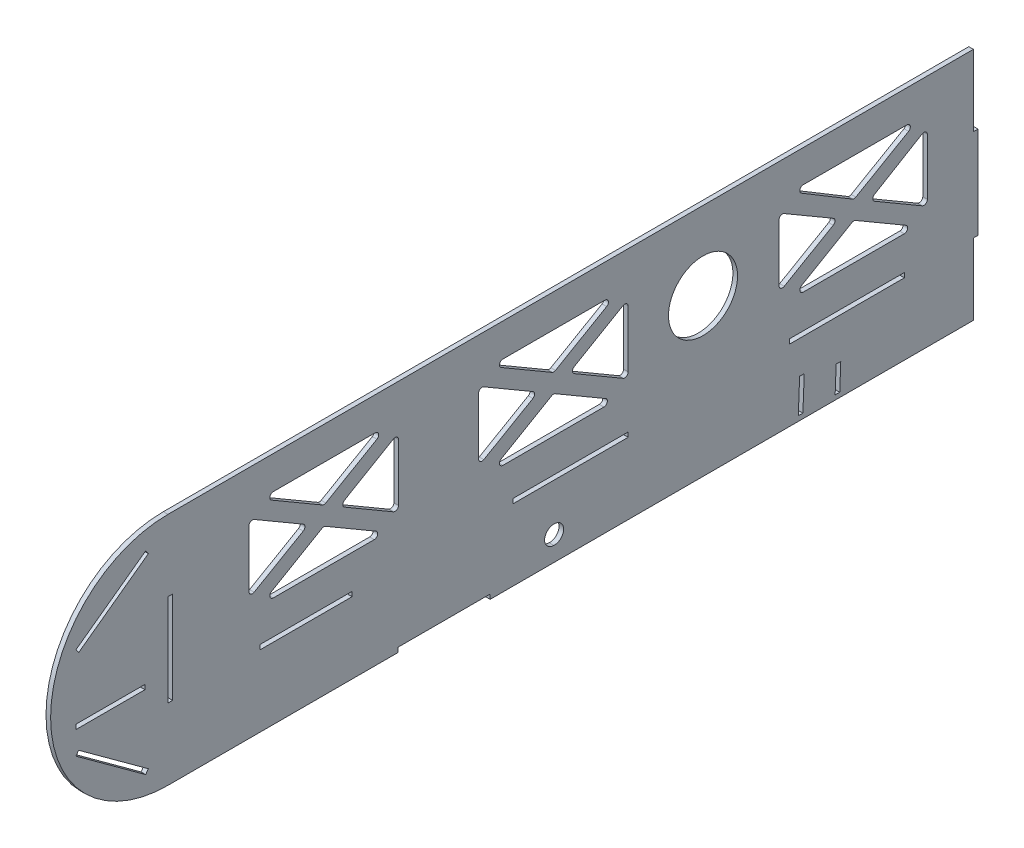
SolidWorks part; units mm, degrees
material "轻木"
ref_plane "前视基准面" through (0, 0, 0) normal (0, 0, 1) x (1, 0, 0)
ref_plane "上视基准面" through (0, 0, 0) normal (0, 1, 0) x (1, 0, 0)
ref_plane "右视基准面" through (0, 0, 0) normal (1, 0, 0) x (0, 0, -1)
sketch "草图1" plane through (0, 0, 0) normal (1, 0, 0) x (0, 0, -1)
  line L0 (145, -32) -> (145, -43)
  line L1 (0, 51) -> (139, 51)
  line L2 (0, 51) -> (0, -51)
  line L3 (0, -51) -> (350, -51)
  line L4 (350, 51) -> (350, -51)
  line L5 (145, 51) -> (331.5, 51)
  line L6 (151, -49) -> (325.5, -49)
  line L7 (331.5, -32) -> (331.5, -35)
  line L8 (337.5, 51) -> (350, 51)
  line L10 (-40, -10) -> (-10, -10)
  line L11 (-40, -10) -> (-40, -8)
  line L12 (-40, -8) -> (-10, -8)
  line L13 (-10, -10) -> (-10, -8)
  line L49 (-40, 20) -> (-9.6982, 42.0918)
  line L50 (-40, 20) -> (-38.8218, 18.3839)
  line L51 (-9.6982, 42.0918) -> (-8.5199, 40.4757)
  line L52 (-38.8218, 18.3839) -> (-8.5199, 40.4757)
  line L53 (-51, 0) -> (0, 0)
  line L54 (-38.8218, -18.3839) -> (-8.5199, -40.4757)
  line L55 (-9.6982, -42.0918) -> (-8.5199, -40.4757)
  line L56 (-40, -20) -> (-38.8218, -18.3839)
  line L57 (-40, -20) -> (-9.6982, -42.0918)
  line L70 (350, 20) -> (352, 20)
  line L71 (350, 20) -> (350, -20)
  line L72 (352, 20) -> (352, -20)
  line L73 (350, -20) -> (352, -20)
  line L74 (0, 20) -> (0, -20)
  line L75 (0, 20) -> (2, 20)
  line L76 (0, -20) -> (2, -20)
  line L77 (2, 20) -> (2, -20)
  line L78 (139, 51) -> (145, 51)
  line L79 (331.5, 51) -> (337.5, 51)
  line L80 (151, -26) -> (325.5, -26)
  line L81 (151, -49) -> (151, -26)
  line L82 (331.5, -35) -> (331.5, -43)
  line L85 (325.5, -49) -> (331.5, -49)
  line L87 (235, -26) -> (305, -26)
  line L91 (145.5484, 36.6595) -> (189.8851, 36.6595)
  line L92 (135, 29.0479) -> (135, 4.2608)
  line L93 (145.5484, -3.3405) -> (189.4516, -3.3405)
  line L94 (200, 29.3884) -> (200, 4.6116)
  line L95 (176.5069, 15.7043) -> (197.7442, 3.3159)
  line L96 (158.585, 17.9016) -> (137.2558, 30.3436)
  line L97 (137.2514, 2.9626) -> (158.5806, 15.3077)
  line L98 (176.5069, 18.2957) -> (197.7442, 30.6841)
  line L99 (144.7926, 33.8638) -> (166.8743, 20.9828)
  line L100 (190.6365, 33.8613) -> (168.3815, 20.9803)
  line L101 (168.2558, 12.2603) -> (190.2074, -0.5448)
  line L102 (144.7926, -0.5448) -> (166.7442, 12.2603)
  line L103 (276.0709, 37) -> (321.089, 37)
  line L104 (265.5225, 28.9941) -> (265.5225, 4.207)
  line L105 (276.0709, -3.3943) -> (319.9742, -3.3943)
  line L106 (330, 28.9941) -> (330, 4.522)
  line L107 (307.0294, 15.31) -> (327.7442, 3.2264)
  line L108 (289.1076, 17.8477) -> (267.7784, 30.2898)
  line L109 (267.7739, 2.9088) -> (289.1032, 15.2538)
  line L110 (307.0153, 17.893) -> (327.7301, 30.2815)
  line L111 (275.2981, 34.2144) -> (297.3797, 20.9391)
  line L112 (321.8404, 34.2018) -> (298.904, 20.9265)
  line L113 (298.7784, 12.2065) -> (320.73, -0.5987)
  line L114 (275.3151, -0.5987) -> (297.2667, 12.2065)
  line L115 (40, -18) -> (80, -18)
  line L116 (40, -18) -> (40, -20)
  line L117 (80, -18) -> (80, -20)
  line L118 (40, -20) -> (80, -20)
  line L119 (150, -18) -> (200, -18)
  line L120 (150, -18) -> (150, -20)
  line L121 (200, -18) -> (200, -20)
  line L122 (150, -20) -> (200, -20)
  line L123 (270, -18) -> (320, -18)
  line L124 (270, -18) -> (270, -20)
  line L125 (320, -18) -> (320, -20)
  line L126 (270, -20) -> (320, -20)
  line L127 (45.7401, 36.6595) -> (90.0769, 36.6595)
  line L128 (35.1917, 29.0479) -> (35.1917, 4.2608)
  line L129 (45.7401, -3.3405) -> (89.6434, -3.3405)
  line L130 (100.1917, 29.0479) -> (100.1917, 4.271)
  line L131 (76.6986, 15.3638) -> (97.9359, 2.9754)
  line L132 (58.7768, 17.9016) -> (37.4476, 30.3436)
  line L133 (37.4431, 2.9626) -> (58.7724, 15.3077)
  line L134 (76.6986, 17.9552) -> (97.9359, 30.3436)
  line L135 (44.9843, 33.8638) -> (67.066, 20.9828)
  line L136 (90.8283, 33.8613) -> (68.5732, 20.9803)
  line L137 (68.4476, 12.2603) -> (90.3992, -0.5448)
  line L138 (44.9843, -0.5448) -> (66.9359, 12.2603)
  line L139 (100, -49) -> (100, -51)
  line L140 (100, -49) -> (140, -49)
  line L141 (100, -51) -> (140, -51)
  line L142 (140, -49) -> (140, -51)
  arc A0 (0, 51) -> (0, -51) centre (0, 0) ccw
  arc A3 (151, -49) -> (145, -43) centre (151, -43) cw
  arc A44 (331.5, -32) -> (325.5, -26) centre (325.5, -32) ccw
  arc A45 (151, -26) -> (145, -32) centre (151, -32) ccw
  arc A46 (97.9359, 30.3436) -> (100.1917, 29.0479) centre (98.6917, 29.0479) cw
  arc A47 (100.1917, 4.271) -> (97.9359, 2.9754) centre (98.6917, 4.271) cw
  arc A48 (197.7442, 30.6841) -> (200, 29.3884) centre (198.5, 29.3884) cw
  arc A49 (200, 4.6116) -> (197.7442, 3.3159) centre (198.5, 4.6116) cw
  arc A50 (176.5069, 15.7043) -> (176.5069, 18.2957) centre (177.2627, 17) cw
  arc A51 (158.585, 17.9016) -> (158.5806, 15.3077) centre (157.8292, 16.6059) cw
  arc A52 (137.2514, 2.9626) -> (135, 4.2608) centre (136.5, 4.2608) cw
  arc A53 (135, 29.0479) -> (137.2558, 30.3436) centre (136.5, 29.0479) cw
  arc A54 (144.7926, -0.5448) -> (145.5484, -3.3405) centre (145.5484, -1.8405) ccw
  arc A55 (189.4516, -3.3405) -> (190.2074, -0.5448) centre (189.4516, -1.8405) ccw
  arc A56 (168.2558, 12.2603) -> (166.7442, 12.2603) centre (167.5, 10.9646) ccw
  arc A57 (144.7926, 33.8638) -> (145.5484, 36.6595) centre (145.5484, 35.1595) cw
  arc A58 (189.8851, 36.6595) -> (190.6365, 33.8613) centre (189.8851, 35.1595) cw
  arc A59 (168.3815, 20.9803) -> (166.8743, 20.9828) centre (167.6301, 22.2785) cw
  arc A60 (327.7301, 30.2815) -> (330, 28.9941) centre (328.5, 28.9941) cw
  arc A61 (330, 4.522) -> (327.7442, 3.2264) centre (328.5, 4.522) cw
  arc A62 (307.0294, 15.31) -> (307.0153, 17.893) centre (307.7852, 16.6057) cw
  arc A63 (289.1076, 17.8477) -> (289.1032, 15.2538) centre (288.3518, 16.5521) cw
  arc A64 (267.7739, 2.9088) -> (265.5225, 4.207) centre (267.0225, 4.207) cw
  arc A65 (265.5225, 28.9941) -> (267.7784, 30.2898) centre (267.0225, 28.9941) cw
  arc A66 (275.3151, -0.5987) -> (276.0709, -3.3943) centre (276.0709, -1.8943) ccw
  arc A67 (319.9742, -3.3943) -> (320.73, -0.5987) centre (319.9742, -1.8943) ccw
  arc A68 (298.7784, 12.2065) -> (297.2667, 12.2065) centre (298.0225, 10.9108) ccw
  arc A69 (275.2981, 34.2144) -> (276.0709, 37) centre (276.0709, 35.5) cw
  arc A70 (321.089, 37) -> (321.8404, 34.2018) centre (321.089, 35.5) cw
  arc A71 (298.904, 20.9265) -> (297.3797, 20.9391) centre (298.1526, 22.2247) cw
  circle A72 centre (232.5, 17) radius 15
  arc A73 (76.6986, 15.3638) -> (76.6986, 17.9552) centre (77.4544, 16.6595) cw
  arc A74 (58.7768, 17.9016) -> (58.7724, 15.3077) centre (58.021, 16.6059) cw
  arc A75 (37.4431, 2.9626) -> (35.1917, 4.2608) centre (36.6917, 4.2608) cw
  arc A76 (35.1917, 29.0479) -> (37.4476, 30.3436) centre (36.6917, 29.0479) cw
  arc A77 (44.9843, -0.5448) -> (45.7401, -3.3405) centre (45.7401, -1.8405) ccw
  arc A78 (89.6434, -3.3405) -> (90.3992, -0.5448) centre (89.6434, -1.8405) ccw
  arc A79 (68.4476, 12.2603) -> (66.9359, 12.2603) centre (67.6917, 10.9646) ccw
  arc A80 (44.9843, 33.8638) -> (45.7401, 36.6595) centre (45.7401, 35.1595) cw
  arc A81 (90.0769, 36.6595) -> (90.8283, 33.8613) centre (90.0769, 35.1595) cw
  arc A82 (68.5732, 20.9803) -> (67.066, 20.9828) centre (67.8218, 22.2785) cw
  arc A83 (325.5, -49) -> (331.5, -43) centre (325.5, -43) ccw
  point P5 (40.1917, 36.6595)
  point P7 (331.5, -49)
  point P8 (286.5, 50)
  point P21 (145, -49)
  point P24 (95.6629, 36.6595)
  point P28 (40.1917, -3.3405)
  point P29 (95.1917, -3.3405)
  point P30 (40.1917, -3.3405)
  point P31 (35.1917, 1.6595)
  point P32 (100, -49)
  point P33 (100.1917, 1.6595)
  point P34 (100.1917, 31.6595)
  point P35 (35.1917, 31.6595)
  point P53 (140, 36.6595)
  point P58 (195.4712, 36.6595)
  point P59 (140, -3.3405)
  point P60 (195, -3.3405)
  point P61 (140, -3.3405)
  point P62 (135, 1.6595)
  point P63 (200, 2)
  point P64 (200, 32)
  point P65 (135, 31.6595)
  point P113 (270.5225, 37)
  point P118 (325.9937, 37)
  point P119 (270.5225, -3.3943)
  point P120 (325.5225, -3.3943)
  point P121 (270.5225, -3.3943)
  point P122 (265.5225, 1.6057)
  point P123 (330, 1.6057)
  point P124 (330, 31.6057)
  point P125 (265.5225, 31.6057)
  point P169 (350, -20)
  point P182 (-9.6982, -42.0918)
  point P184 (-40, -20)
  point P189 (352, 20)
  point P190 (352, -20)
  point P198 (350, 20)
  dimension "D1" = 1.5
  dimension "D2" = 1.5
  dimension "D3" = 1.5
  dimension "D5" = 1.5
  dimension "D6" = 1.5
  dimension "D7" = 1.5
  dimension "D8" = 1.5
  dimension "D9" = 1.5
  dimension "D10" = 1.5
  dimension "D11" = 1.5
  dimension "D12" = 1.5
  dimension "D13" = 1.5
  dimension "D14" = 1.5
  dimension "D15" = 1.5
  dimension "D16" = 1.5
  dimension "D17" = 1.5
  dimension "D18" = 1.5
  dimension "D19" = 1.5
  dimension "D20" = 1.5
  dimension "D21" = 1.5
  dimension "D22" = 1.5
  dimension "D23" = 1.5
  dimension "D24" = 1.5
  dimension "D25" = 1.5
  dimension "D26" = 1.5
  dimension "D27" = 1.5
  dimension "D28" = 1.5
  dimension "D29" = 1.5
  dimension "D30" = 1.5
  dimension "D31" = 1.5
  dimension "D32" = 1.5
  dimension "D33" = 1.5
  dimension "D34" = 1.5
  dimension "D35" = 1.5
  dimension "D36" = 1.5
  dimension "D37" = 1.5
  dimension "D38" = 6
  dimension "D41" = 2
  dimension "D42" = 37.5
  dimension "D43" = 2
extrude "凸台-拉伸3" add sketch "草图1" along normal blind 2
sketch "草图2" plane through (2, 0, 0) normal (1, 0, 0) x (0, 0, -1)
  line L1 (142.7525, -50.0704) -> (332.831, -50.0704)
  line L2 (142.7525, -50.0704) -> (142.7525, -23.3968)
  line L3 (142.7525, -23.3968) -> (332.831, -23.3968)
  line L4 (332.831, -50.0704) -> (332.831, -23.3968)
extrude "凸台-拉伸4" add sketch "草图2" against normal blind 2
sketch "草图3" plane through (0, 0, 0) normal (-1, 0, 0) x (0, 0, 1)
  line L0 (-276.4747, -34.6355) -> (-274.4884, -34.25)
  line L1 (-275.9107, -48.8709) -> (-276.4747, -34.6355)
  line L2 (-273.9093, -48.8651) -> (-274.4884, -34.25)
  line L3 (-273.9093, -48.8651) -> (-275.9107, -48.8709)
  line L4 (-273.9093, -48.8651) -> (-275.9107, -48.8709)
  line L5 (-273.9093, -48.8651) -> (-274.4884, -34.25)
  line L6 (-275.9107, -48.8709) -> (-276.4747, -34.6355)
  line L8 (-292.3526, -38.0349) -> (-290.3684, -37.5972)
  line L9 (-291.9181, -49) -> (-292.3526, -38.0349)
  line L10 (-289.9168, -48.9942) -> (-290.3684, -37.5972)
  line L11 (-289.9168, -48.9942) -> (-291.9181, -49)
  line L12 (-289.9168, -48.9942) -> (-291.9181, -49)
  line L13 (-289.9168, -48.9942) -> (-290.3684, -37.5972)
  line L14 (-291.9181, -49) -> (-292.3526, -38.0349)
  line L16 (-274.4884, -34.25) -> (-276.4869, -34.3291)
  line L17 (-276.4747, -34.6355) -> (-276.4869, -34.3291)
  line L18 (-290.3684, -37.5972) -> (-292.3668, -37.6764)
  line L19 (-292.3526, -38.0349) -> (-292.3668, -37.6764)
  circle A0 centre (-167.6608, -40.5184) radius 4
  circle A1 centre (-167.6608, -40.5184) radius 4
extrude "切除-拉伸1" cut sketch "草图3" against normal blind 2 contours L17 L6 L4 L5 L16 | L14 L19 L18 L13 L12
sketch "草图4" plane through (2, 0, 0) normal (1, 0, 0) x (0, 0, -1)
  circle A0 centre (167.9276, -40.5289) radius 4
  arc A1 (167.6359, -44.5183) -> (167.9525, -36.529) centre (167.9276, -40.5289) ccw
  circle A2 centre (167.6608, -40.5184) radius 4 construction
  arc A3 (167.9525, -36.529) -> (167.6359, -44.5183) centre (167.6608, -40.5184) ccw
extrude "切除-拉伸2" cut sketch "草图4" against normal blind 2
